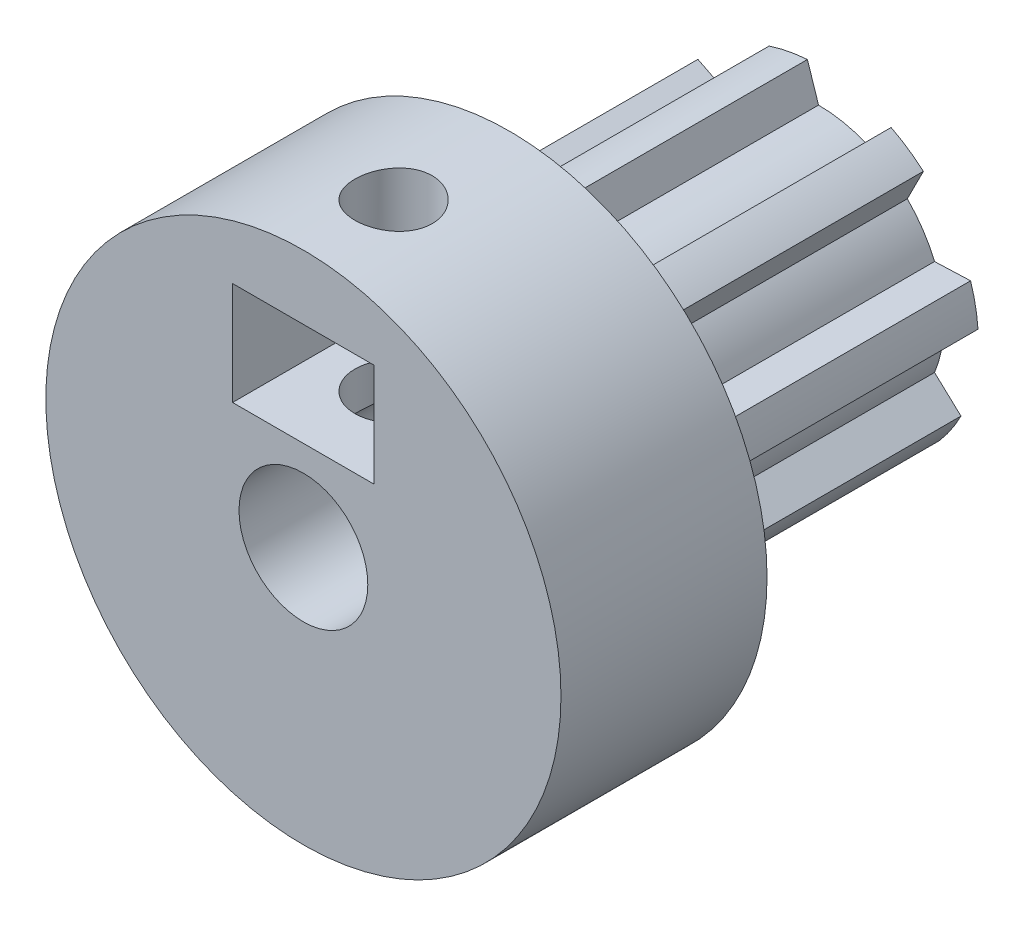
SolidWorks part; units mm, degrees
ref_plane "Front Plane" through (0, 0, 0) normal (0, 0, 1) x (1, 0, 0)
ref_plane "Top Plane" through (0, 0, 0) normal (0, 1, 0) x (1, 0, 0)
ref_plane "Right Plane" through (0, 0, 0) normal (1, 0, 0) x (0, 0, -1)
ref_plane "Plane1" through (0, 0, 26) normal (0, 0, 1) x (1, 0, 0)
sketch "Sketch1" plane through (0, 0, 26) normal (0, 0, 1) x (1, 0, 0)
  line L0 (4.8737, 0) -> (6.1903, 0.4329)
  line L1 (5.9017, 1.9176) -> (4.5027, 1.8651)
  line L2 (3.4462, 3.4462) -> (4.0711, 4.6833)
  line L3 (2.8172, 5.529) -> (1.8651, 4.5027)
  line L4 (0, 4.8737) -> (-0.4329, 6.1903)
  line L5 (-1.9176, 5.9017) -> (-1.8651, 4.5027)
  line L6 (-3.4462, 3.4462) -> (-4.6833, 4.0711)
  line L7 (-5.529, 2.8172) -> (-4.5027, 1.8651)
  line L8 (-4.8737, 0) -> (-6.1903, -0.4329)
  line L9 (-5.9017, -1.9176) -> (-4.5027, -1.8651)
  line L10 (-3.4462, -3.4462) -> (-4.0711, -4.6833)
  line L11 (-2.8172, -5.529) -> (-1.8651, -4.5027)
  line L12 (0, -4.8737) -> (0.4329, -6.1903)
  line L13 (1.9176, -5.9017) -> (1.8651, -4.5027)
  line L14 (3.4462, -3.4462) -> (4.6833, -4.0711)
  line L15 (5.529, -2.8172) -> (4.5027, -1.8651)
  arc A0 (4.5027, -1.8651) -> (4.8737, 0) centre (0, 0) ccw
  arc A1 (6.1903, 0.4329) -> (5.9017, 1.9176) centre (0, 0) ccw
  arc A2 (4.5027, 1.8651) -> (3.4462, 3.4462) centre (0, 0) ccw
  arc A3 (4.0711, 4.6833) -> (2.8172, 5.529) centre (0, 0) ccw
  arc A4 (1.8651, 4.5027) -> (0, 4.8737) centre (0, 0) ccw
  arc A5 (-0.4329, 6.1903) -> (-1.9176, 5.9017) centre (0, 0) ccw
  arc A6 (-1.8651, 4.5027) -> (-3.4462, 3.4462) centre (0, 0) ccw
  arc A7 (-4.6833, 4.0711) -> (-5.529, 2.8172) centre (0, 0) ccw
  arc A8 (-4.5027, 1.8651) -> (-4.8737, 0) centre (0, 0) ccw
  arc A9 (-6.1903, -0.4329) -> (-5.9017, -1.9176) centre (0, 0) ccw
  arc A10 (-4.5027, -1.8651) -> (-3.4462, -3.4462) centre (0, 0) ccw
  arc A11 (-4.0711, -4.6833) -> (-2.8172, -5.529) centre (0, 0) ccw
  arc A12 (-1.8651, -4.5027) -> (0, -4.8737) centre (0, 0) ccw
  arc A13 (0.4329, -6.1903) -> (1.9176, -5.9017) centre (0, 0) ccw
  arc A14 (1.8651, -4.5027) -> (3.4462, -3.4462) centre (0, 0) ccw
  arc A15 (4.6833, -4.0711) -> (5.529, -2.8172) centre (0, 0) ccw
  circle A16 centre (0, 0) radius 5.5612 construction
  point P34 (5.5567, 0.2246)
  point P35 (3.7704, 4.088)
  dimension "D1" = 11.1225
  dimension "D4" = 0.6442
  dimension "D5" = 0.6875
  dimension "D2" = 30.5745
  dimension "D3" = 16.051
extrude "Boss-Extrude1" add sketch "Sketch1" against normal blind 12
sketch "Sketch2" plane through (0, 0, 26) normal (0, 0, 1) x (1, 0, 0)
  circle A0 centre (0, 0) radius 10
  dimension "D1" = 20
extrude "Boss-Extrude2" add sketch "Sketch2" along normal blind 8
hole_wizard "Ø5.0 (5) Diameter Hole1" positions "Sketch5" profile "Sketch4" hole size "Ø5.0" standard "Ansi Metric"
sketch "Sketch5" plane through (0, 0, 14) normal (0, 0, -1) x (-1, 0, 0)
  point P0 (0, 0)
sketch "Sketch4" plane through (0, 0, 14) normal (1, 0, 0) x (0, 1, 0)
  line L0 (0, 0) -> (0, 26.5022)
  line L1 (0, 26.5022) -> (2.5, 25)
  line L2 (2.5, 25) -> (2.5, 0)
  line L5 (2.5, 0) -> (0, 0)
  line L10 (0, 26.5022) -> (-2.5, 25) construction
  line L11 (0, -6.35) -> (0, 107.95) construction
  dimension "Hole Dia." = 5
  dimension "Hole Depth" = 25
  dimension "Drill Angle" = 118
sketch "Sketch6" plane through (0, 0, 0) normal (0, 1, 0) x (1, 0, 0)
  line L0 (0, -55) -> (0, 55) construction
  line L1 (-10, -34) -> (10, -34) construction
  circle A0 centre (0, -30.5) radius 1.5
  point P4 (0, -34)
  dimension "D1" = 3
  dimension "D2" = 3.5
extrude "Cut-Extrude1" cut sketch "Sketch6" along normal blind 11
ref_plane "Plane2" through (0, 3.5, 0) normal (0, 1, 0) x (-1, 0, 0)
sketch "Sketch8" plane through (0, 3.5, 0) normal (0, 1, 0) x (-1, 0, 0)
  line L0 (-2.75, 32.0877) -> (-2.75, 34)
  line L1 (-2.75, 32.0877) -> (-2.75, 28.9123)
  line L2 (-2.75, 28.9123) -> (0, 27.3246)
  line L3 (0, 27.3246) -> (2.75, 28.9123)
  line L4 (2.75, 28.9123) -> (2.75, 32.0877)
  line L5 (2.75, 32.0877) -> (0, 33.6754) construction
  line L6 (0, 33.6754) -> (-2.75, 32.0877) construction
  line L7 (10, 34) -> (-10, 34) construction
  line L8 (-2.75, 34) -> (2.75, 34)
  line L9 (2.75, 34) -> (2.75, 32.0877)
  circle A0 centre (0, 30.5) radius 1.5 construction
  circle A1 centre (0, 30.5) radius 1.5
  circle A2 centre (0, 30.5) radius 2.75 construction
  dimension "D1" = 5.5
extrude "Cut-Extrude2" cut sketch "Sketch8" along normal blind 4
pattern_circular "CirPattern1" [suppressed] count 2 every 180
sketch "Sketch9" plane through (0, 3.5, 0) normal (0, 1, 0) x (-1, 0, 0)
  line L0 (-3, 32.2321) -> (-3, 34)
  line L1 (-3, 28.7679) -> (0, 27.0359)
  line L2 (0, 27.0359) -> (3, 28.7679)
  line L3 (3, 28.7679) -> (3, 32.2321)
  line L4 (3, 32.2321) -> (0, 33.9641) construction
  line L5 (0, 33.9641) -> (-3, 32.2321) construction
  line L6 (-3, 32.2321) -> (-3, 28.7679)
  line L7 (10, 34) -> (-10, 34) construction
  line L8 (-3, 34) -> (3, 34)
  line L9 (3, 34) -> (3, 32.2321)
  circle A0 centre (0, 30.5) radius 1.5 construction
  circle A1 centre (0, 30.5) radius 1.5 construction
  circle A2 centre (0, 30.5) radius 3 construction
  dimension "D1" = 6
extrude "Cut-Extrude3" [suppressed] cut sketch "Sketch9" along normal blind 4.5
